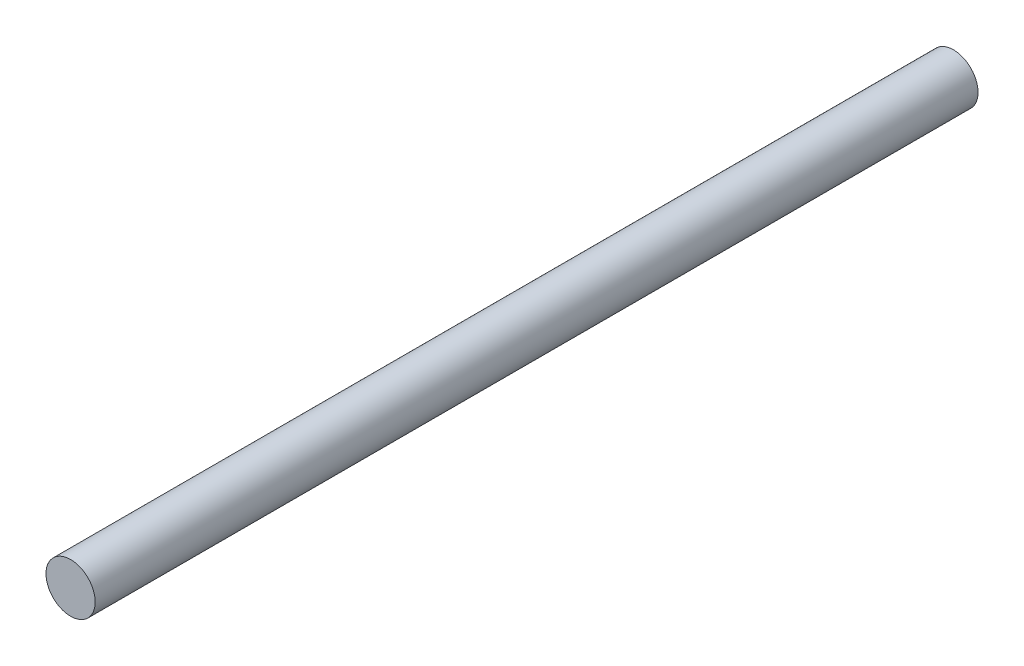
SolidWorks part; units mm, degrees
ref_plane "Front Plane" through (0, 0, 0) normal (0, 0, 1) x (1, 0, 0)
ref_plane "Top Plane" through (0, 0, 0) normal (0, 1, 0) x (1, 0, 0)
ref_plane "Right Plane" through (0, 0, 0) normal (1, 0, 0) x (0, 0, -1)
ref_plane "Plane1" through (0, 0, 0) normal (0, -1, 0) x (1, 0, 0)
sketch "Sketch1" plane through (0, 0, 0) normal (0, -1, 0) x (1, 0, 0)
  line L0 (3.9, 180) -> (0, 180)
  line L1 (0, 180) -> (0, 40)
  line L2 (0, 40) -> (3.9, 40)
  line L3 (3.9, 40) -> (3.9, 180)
  line L4 (0, 180) -> (0, 40) construction
  dimension "D1" = 3.9
  dimension "D2" = 140
revolve "Revolve1" add sketch "Sketch1" angle 360 about L4
